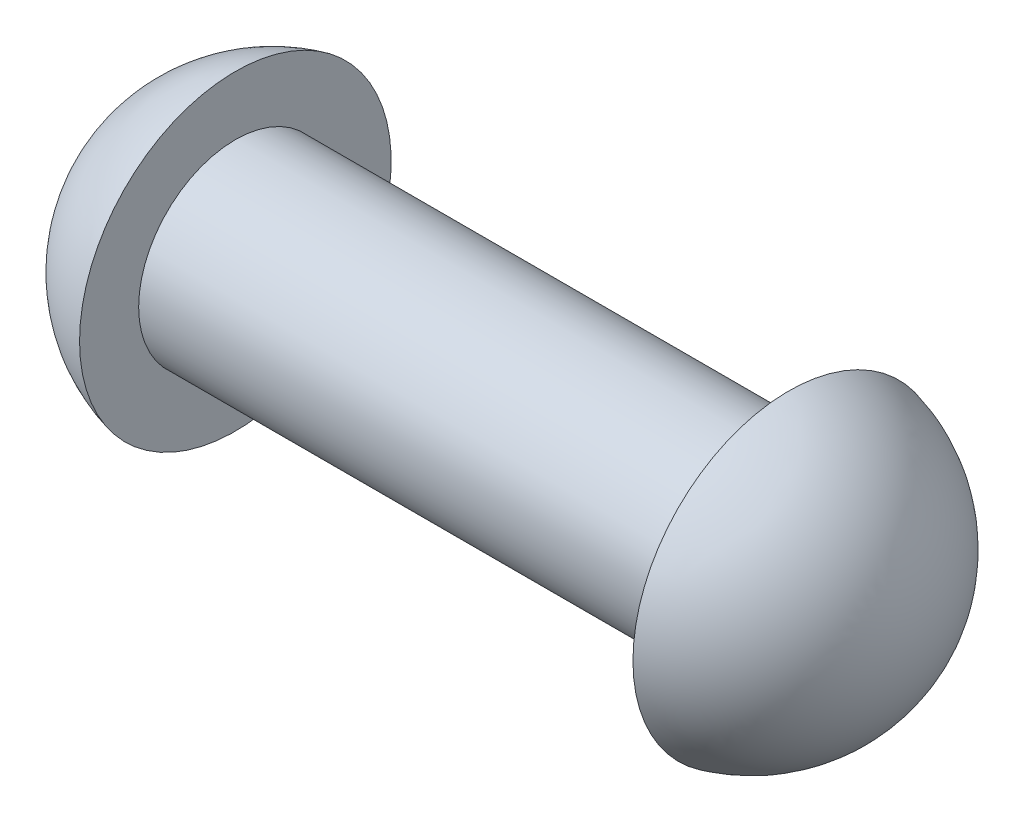
SolidWorks part; units mm, degrees
ref_plane "Plane1" through (0, 0, 0) normal (0, 0, 1) x (1, 0, 0)
ref_plane "Plane2" through (0, 0, 0) normal (0, 1, 0) x (1, 0, 0)
ref_plane "Plane3" through (0, 0, 0) normal (1, 0, 0) x (0, 0, -1)
sketch "Sketch1" plane through (0, 0, 0) normal (0, 0, 1) x (1, 0, 0)
  line L0 (-138, 0) -> (13, 0) construction
  line L1 (-126, 0) -> (0, 0)
  line L2 (-103, 18) -> (-103, 29)
  line L3 (-103, 18) -> (0, 18)
  line L4 (0, 18) -> (0, 0)
  arc A0 (-103, 29) -> (-126, 0) centre (-96.0005, -0.172) ccw
  point P12 (-103, 18)
  dimension "HeadRadius" = 30
  dimension "Diameter" = 36
  dimension "GripLength" = 103
  dimension "HeadHt" = 23
  dimension "HeadDia" = 58
revolve "Base-Revolve" add sketch "Sketch1" angle 360 about L0
sketch "Sketch2" plane through (0, 0, 0) normal (0, 0, 1) x (1, 0, 0)
  line L0 (-49, 0) -> (71, 0) construction
  line L1 (0, 0) -> (23, 0)
  line L2 (0, 0) -> (0, 29)
  arc A0 (23, 0) -> (0, 29) centre (-6.9995, -0.172) ccw
  dimension "D3" = 30
  dimension "D1" = 58
  dimension "D2" = 23
revolve "HeadTypeA" add sketch "Sketch2" angle 360 about L0
sketch "Sketch3" plane through (0, 0, 0) normal (0, 0, 1) x (1, 0, 0)
  line L0 (6, 0) -> (-54, 0) construction
  line L1 (-138, 0) -> (13, 0) construction
  line L2 (0, 0) -> (0, 26)
  line L3 (0, 26) -> (-19.3137, 18)
  line L4 (0, -26) -> (-19.3137, -18) construction
  line L6 (-19.3137, 0) -> (-19.3137, 18)
  line L7 (-19.3137, 0) -> (0, 0)
  dimension "HeadDia" = 52
  dimension "D1" = 36
  dimension "HeadAng" = 45
revolve "HeadTypeB" [suppressed] add sketch "Sketch3" angle 360 about L0
equation "\"D1@Sketch2\" = \"HeadDia@Sketch1\""
equation "\"D2@Sketch2\" = \"HeadHt@Sketch1\""
equation "\"D3@Sketch2\" = \"HeadRadius@Sketch1\""
equation "\"D1@Sketch3\" = \"Diameter@Sketch1\""
